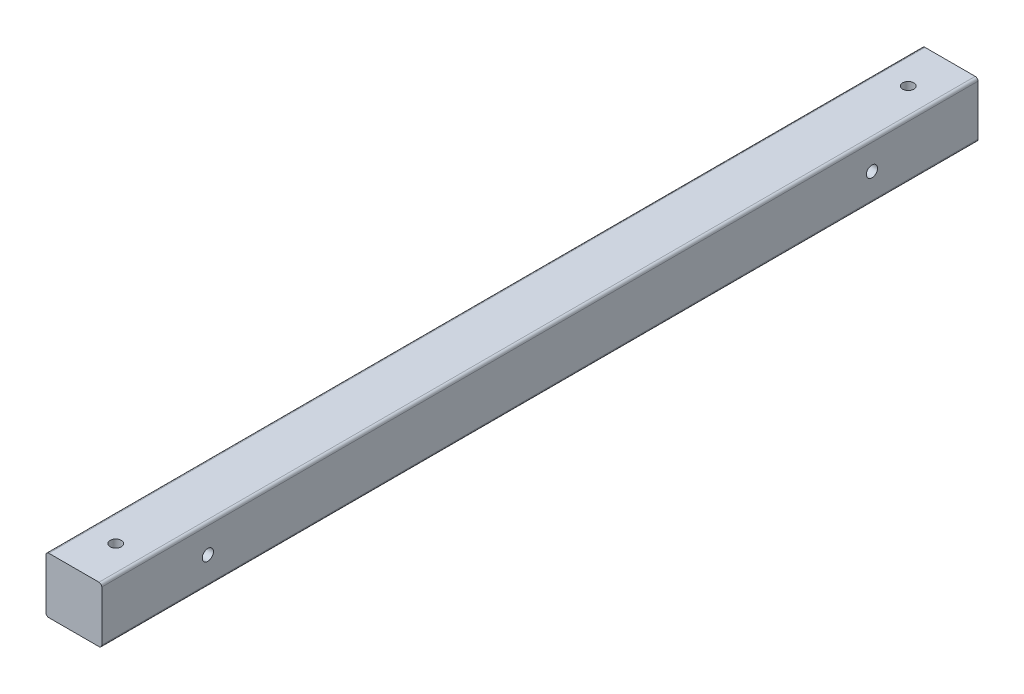
SolidWorks part; units mm, degrees
ref_plane "前视基准面" through (0, 0, 0) normal (0, 0, 1) x (1, 0, 0)
ref_plane "上视基准面" through (0, 0, 0) normal (0, 1, 0) x (1, 0, 0)
ref_plane "右视基准面" through (0, 0, 0) normal (1, 0, 0) x (0, 0, -1)
sketch "草图1" plane through (0, 0, 0) normal (0, 0, 1) x (1, 0, 0)
  line L1 (0, 0) -> (20, 0)
  line L2 (0, 0) -> (0, 20)
  line L3 (0, 20) -> (20, 20)
  line L4 (20, 0) -> (20, 20)
  dimension "D1" = 20
  dimension "D2" = 20
extrude "凸台-拉伸1" add sketch "草图1" along normal blind 314
sketch "草图2" plane through (0, 20, 0) normal (0, 1, 0) x (1, 0, 0)
  line L0 (20, 0) -> (0, 0) construction
  line L1 (20, -314) -> (0, -314) construction
  circle A0 centre (10, -15) radius 2
  circle A1 centre (10, -299) radius 2
  point P8 (10, 0)
  dimension "D3" = 4
  dimension "D1" = 15
  dimension "D2" = 15
extrude "切除-拉伸1" cut sketch "草图2" against normal blind 314
fillet "圆角1" radius 1 4 edges at (0, 0, 157) (20, 0, 157) (0, 20, 157) (20, 20, 157)
sketch "草图3" plane through (0, 0, 0) normal (-1, 0, 0) x (0, 0, 1)
  line L0 (0, 19) -> (0, 1) construction
  line L1 (314, 19) -> (314, 1) construction
  circle A0 centre (38, 10) radius 2
  circle A1 centre (276, 10) radius 2
  point P8 (0, 10)
  dimension "D3" = 4
  dimension "D1" = 38
  dimension "D2" = 38
extrude "切除-拉伸2" cut sketch "草图3" against normal blind 20
